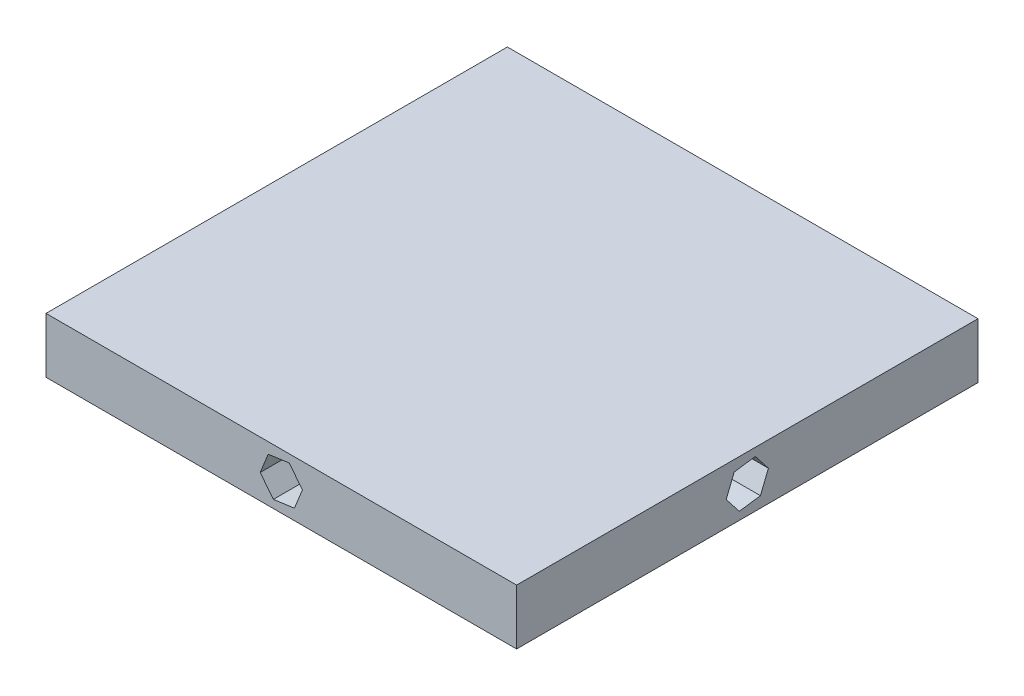
SolidWorks part; units mm, degrees
material "ABS"
ref_plane "Plano frontal" through (0, 0, 0) normal (0, 0, 1) x (1, 0, 0)
ref_plane "Plano superior" through (0, 0, 0) normal (0, 1, 0) x (1, 0, 0)
ref_plane "Plano direito" through (0, 0, 0) normal (1, 0, 0) x (0, 0, -1)
sketch "Esboço2" plane through (0, 0, 0) normal (0, 1, 0) x (1, 0, 0)
  line L7 (25.5, 25) -> (-25.5, 25)
  line L8 (25.5, 25) -> (25.5, -25)
  line L9 (25.5, -25) -> (-25.5, -25)
  line L10 (-25.5, 25) -> (-25.5, -25)
  line L11 (25.5, 25) -> (-25.5, -25) construction
  line L12 (25.5, -25) -> (-25.5, 25) construction
  point P0 (0, 0)
  dimension "D1" = 50
  dimension "D2" = 51
extrude "Ressalto-extrusão2" add sketch "Esboço2" along normal blind 6
sketch "Esboço3" plane through (25.5, 0, 0) normal (-1, 0, 0) x (0, 0, 1)
  line L1 (-1.4218, 1.1802) -> (0.8651, 0.8588)
  line L2 (0.8651, 0.8588) -> (2.2869, 2.6786)
  line L3 (2.2869, 2.6786) -> (1.4218, 4.8198)
  line L4 (1.4218, 4.8198) -> (-0.8651, 5.1412)
  line L5 (-0.8651, 5.1412) -> (-2.2869, 3.3214)
  line L6 (-2.2869, 3.3214) -> (-1.4218, 1.1802)
  line L9 (25, 0) -> (-25, 0) construction
  circle A0 centre (0, 3) radius 2 construction
  dimension "D1" = 4
  dimension "D2" = 8
  dimension "D3" = 3
extrude "Corte-extrusão1" cut sketch "Esboço3" along normal blind 15 from offset 1 offset against normal yes
pattern_circular "PadrãoCircular1" count 4 over 360 about axis through (0, 0, 0) along (0, 1, 0) of "Corte-extrusão1"
